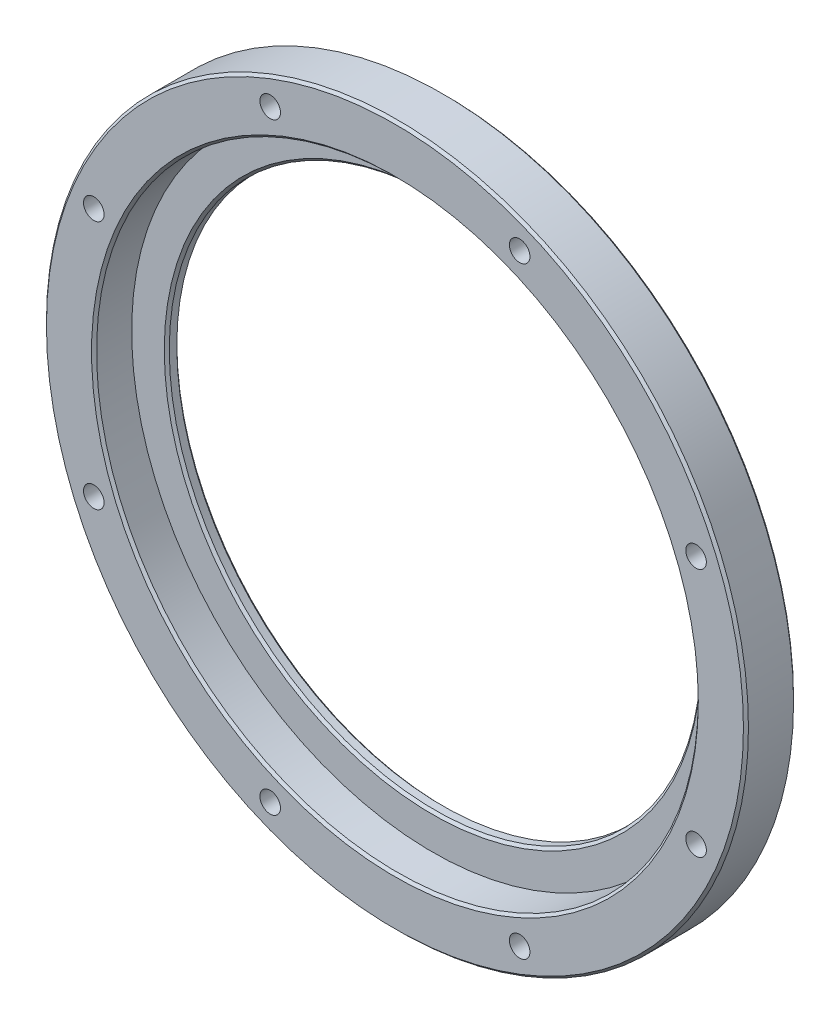
SolidWorks part; units mm, degrees
ref_plane "Front Plane" through (0, 0, 0) normal (0, 0, 1) x (1, 0, 0)
ref_plane "Top Plane" through (0, 0, 0) normal (0, 1, 0) x (1, 0, 0)
ref_plane "Right Plane" through (0, 0, 0) normal (1, 0, 0) x (0, 0, -1)
ref_plane "Plane1" through (0, 0, 0) normal (0, -1, 0) x (1, 0, 0)
sketch "Sketch1" plane through (0, 0, 0) normal (0, -1, 0) x (1, 0, 0)
  line L0 (140, 20) -> (0, 20)
  line L1 (0, 20) -> (0, 0)
  line L2 (0, 0) -> (140, 0)
  line L3 (140, 0) -> (140, 20)
  line L4 (0, 20) -> (0, 0) construction
  dimension "D1" = 20
  dimension "D2" = 140
revolve "Revolve1" add sketch "Sketch1" angle 360 about L4
hole_wizard "Ø8.2 (8.2) Diameter Hole1" positions "Sketch3" profile "Sketch2" hole size "Ø8.2" standard "ANSI Metric"
sketch "Sketch3" plane through (0, 0, 20) normal (0, 0, 1) x (1, 0, 0)
  point P0 (49.7488, 120.1043)
  point P1 (120.1043, 49.7488)
  point P2 (120.1043, -49.7488)
  point P3 (49.7488, -120.1043)
  point P4 (-49.7488, -120.1043)
  point P5 (-120.1043, -49.7488)
  point P6 (-120.1043, 49.7488)
  point P7 (-49.7488, 120.1043)
sketch "Sketch2" plane through (49.7488, 120.1043, 20) normal (1, 0, 0) x (0, -1, 0)
  line L0 (0, 0) -> (0, 20)
  line L1 (0, 20) -> (4.1, 20)
  line L2 (4.1, 20) -> (4.1, 0)
  line L5 (4.1, 0) -> (0, 0)
  line L11 (0, -6.35) -> (0, 107.95) construction
  dimension "Thru Hole Dia." = 8.2
  dimension "Thru Hole Depth" = 20
hole_wizard "Hole1" positions "Sketch5" profile "Sketch4" legacy
sketch "Sketch5" plane through (0, 0, 20) normal (0, 0, 1) x (1, 0, 0)
  point P0 (0, 0)
sketch "Sketch4" plane through (0, 0, 20) normal (1, 0, 0) x (0, -1, 0)
  line L0 (0, 0) -> (0, 20)
  line L1 (0, 20) -> (106, 20)
  line L2 (106, 20) -> (106, 15)
  line L3 (106, 15) -> (120, 15)
  line L4 (120, 15) -> (120, 0)
  line L5 (120, 0) -> (0, 0)
  line L6 (0, 110) -> (0, -10) construction
  dimension "Diameter" = 212
  dimension "Depth" = 20
  dimension "C-Bore Diameter" = 240
  dimension "C-Bore Depth" = 15
chamfer "Chamfer1" distance 1 angle 45 5 edges at (-140, 0, 0) (106, 0, 0) (106, 0, 5) (120, 0, 20) (-140, 0, 20)
